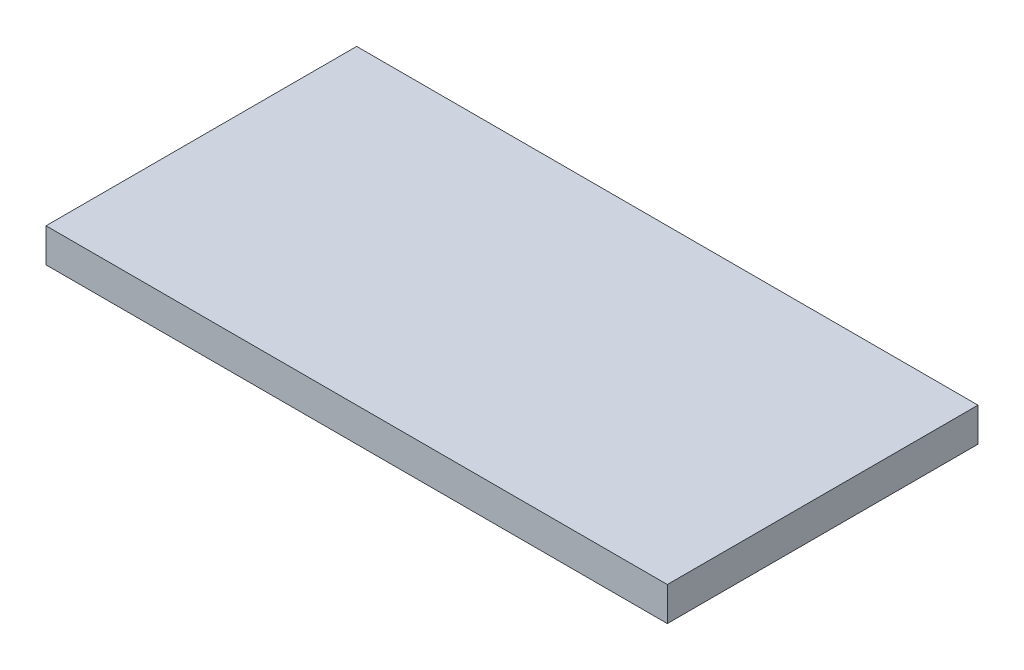
SolidWorks part; units mm, degrees
ref_plane "Plano frontal" through (0, 0, 0) normal (0, 0, 1) x (1, 0, 0)
ref_plane "Plano superior" through (0, 0, 0) normal (0, 1, 0) x (1, 0, 0)
ref_plane "Plano direito" through (0, 0, 0) normal (1, 0, 0) x (0, 0, -1)
sketch "Esboço2" plane through (0, 0, 0) normal (0, 0, 1) x (1, 0, 0)
  line L0 (-58, 0) -> (0, 0)
  line L1 (0, 0) -> (58, 0)
  line L2 (58, 0) -> (58, 6.3221)
  line L3 (58, 6.3221) -> (0, 6.3221)
  line L4 (0, 6.3221) -> (-58, 6.3221)
  line L5 (-58, 6.3221) -> (-58, 0)
  dimension "D1" = 116
extrude "Ressalto-extrusão1" add sketch "Esboço2" against normal blind 58
sketch "Esboço3" plane through (0, 6.3221, 0) normal (0, 1, 0) x (1, 0, 0)
  line L10 (-43.9992, 42) -> (-24.7992, 42)
  line L13 (-43.9992, 16) -> (-24.7992, 16)
  line L31 (43.9992, 42) -> (24.7992, 42)
  line L32 (43.9992, 16) -> (24.7992, 16)
  arc A2 (24.7992, 42) -> (-24.7992, 42) centre (0, 29) ccw
  arc A3 (-43.9992, 16) -> (-43.9992, 42) centre (-43.9992, 29) cw
  arc A5 (43.9992, 42) -> (43.9992, 16) centre (43.9992, 29) cw
  arc A8 (-24.7992, 16) -> (24.7992, 16) centre (0, 29) ccw
  dimension "D2" = 56
  dimension "D1" = 13
  dimension "D3" = 13
  dimension "D4" = 19.2
